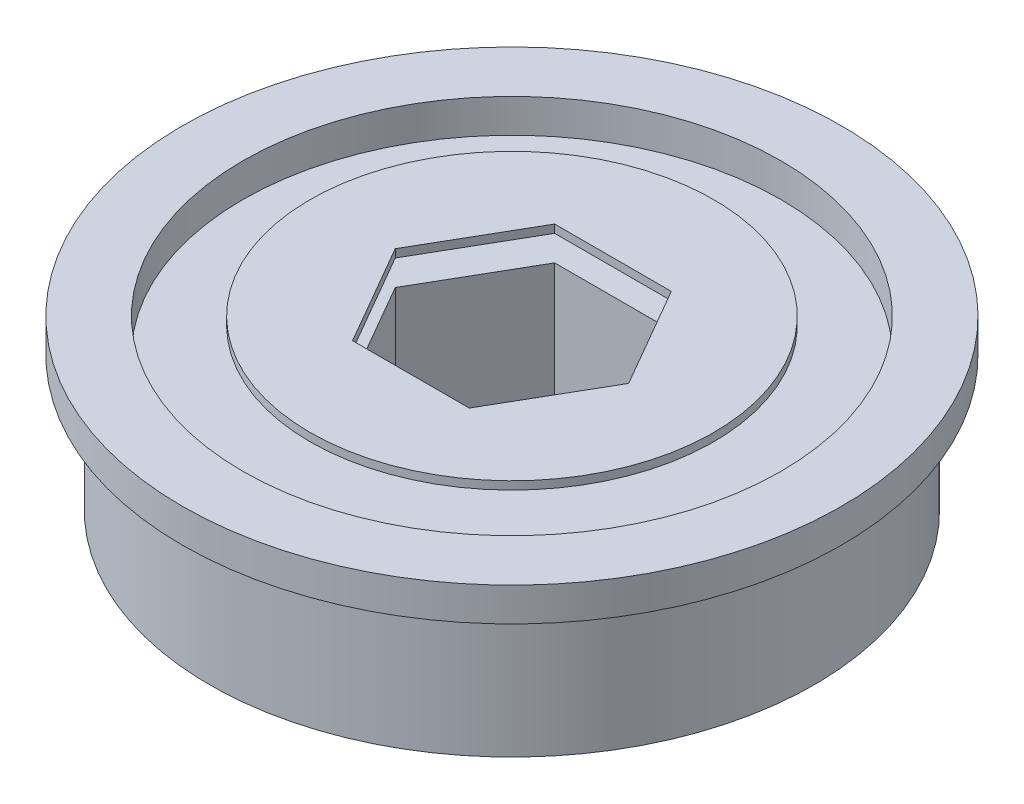
SolidWorks part; units mm, degrees
ref_plane "Front Plane" through (0, 0, 0) normal (0, 0, 1) x (1, 0, 0)
ref_plane "Top Plane" through (0, 0, 0) normal (0, 1, 0) x (1, 0, 0)
ref_plane "Right Plane" through (0, 0, 0) normal (1, 0, 0) x (0, 0, -1)
ref_plane "Plane1" through (0, 0, 0) normal (0, 0, -1) x (-1, 0, 0)
sketch "Sketch1" plane through (0, 0, 0) normal (0, 0, -1) x (-1, 0, 0)
  line L0 (-15.5575, 6.35) -> (0, 6.35)
  line L1 (0, 6.35) -> (0, 7.9375)
  line L2 (0, 7.9375) -> (-15.5575, 7.9375)
  line L3 (-15.5575, 7.9375) -> (-15.5575, 6.35)
  line L4 (0, 6.35) -> (0, 7.9375) construction
revolve "Revolve1" add sketch "Sketch1" angle 360 about L4
hole_wizard "1 (1) Diameter Hole1" positions "Sketch3" profile "Sketch2" hole size "1" standard "ANSI Inch"
sketch "Sketch3" plane through (0, 7.9375, 0) normal (0, 1, 0) x (1, 0, 0)
  point P0 (0, 0)
sketch "Sketch2" plane through (0, 7.9375, 0) normal (1, 0, 0) x (0, 0, 1)
  line L0 (0, 0) -> (0, 1.5875)
  line L1 (0, 1.5875) -> (12.7, 1.5875)
  line L2 (12.7, 1.5875) -> (12.7, 0)
  line L5 (12.7, 0) -> (0, 0)
  line L11 (0, -6.35) -> (0, 107.95) construction
  dimension "Thru Hole Dia." = 25.4
  dimension "Thru Hole Depth" = 1.5875
ref_plane "Plane2" through (0, 7.5565, 0) normal (0, -1, 0) x (1, 0, 0)
sketch "Sketch4" plane through (0, 7.5565, 0) normal (0, -1, 0) x (1, 0, 0)
  circle A0 centre (0, 0) radius 9.525
extrude "Boss-Extrude1" add sketch "Sketch4" against normal blind 0.381
sketch "Sketch5" plane through (0, 6.35, 0) normal (0, -1, 0) x (1, 0, 0)
  circle A0 centre (0, 0) radius 14.2748
extrude "Boss-Extrude2" add sketch "Sketch5" along normal blind 6.35
sketch "Sketch6" plane through (0, 0, 0) normal (0, -1, 0) x (1, 0, 0)
  line L0 (-5.5079, 0) -> (-2.754, -4.77)
  line L1 (-2.754, -4.77) -> (2.754, -4.77)
  line L2 (2.754, -4.77) -> (5.5079, 0)
  line L3 (5.5079, 0) -> (2.754, 4.77)
  line L4 (2.754, 4.77) -> (-2.754, 4.77)
  line L5 (-2.754, 4.77) -> (-5.5079, 0)
extrude "Cut-Extrude1" cut sketch "Sketch6" against normal through all
